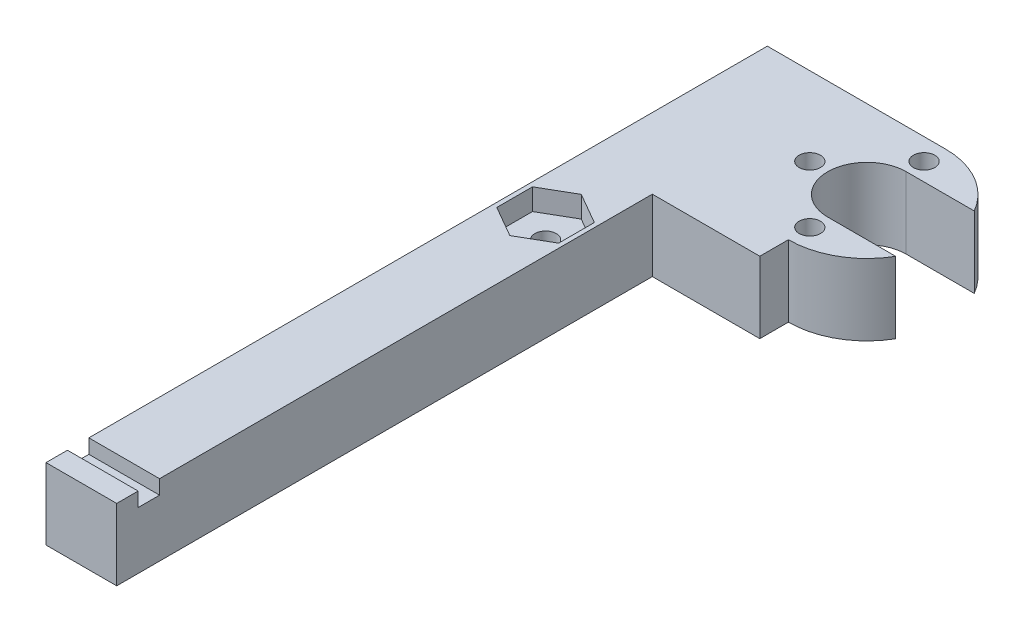
SolidWorks part; units mm, degrees
ref_plane "Front Plane" through (0, 0, 0) normal (0, 0, 1) x (1, 0, 0)
ref_plane "Top Plane" through (0, 0, 0) normal (0, 1, 0) x (1, 0, 0)
ref_plane "Right Plane" through (0, 0, 0) normal (1, 0, 0) x (0, 0, -1)
sketch "Sketch1" plane through (0, 0, 0) normal (0, 1, 0) x (1, 0, 0)
  line L0 (0, 0) -> (0, -75)
  line L1 (0, -75) -> (9.9, -75)
  line L2 (9.9, -75) -> (9.9, 0)
  line L3 (9.9, 0) -> (24.95, 0)
  line L4 (24.95, 0) -> (24.95, 4)
  line L5 (0, 0) -> (0, 26)
  line L6 (0, 26) -> (24.95, 26)
  circle A0 centre (24.95, 15) radius 5.5
  arc A1 (24.95, 4) -> (24.95, 26) centre (24.95, 15) ccw
  circle A2 centre (24.95, 23) radius 1.5
  circle A3 centre (24.95, 7) radius 1.5
  circle A4 centre (16.95, 15) radius 1.5
  point P7 (4.95, -75)
  dimension "D5" = 11
  dimension "D6" = 11
  dimension "D7" = 3
  dimension "D9" = 3
  dimension "D11" = 3
  dimension "D1" = 75
  dimension "D2" = 9.9
  dimension "D3" = 20
  dimension "D4" = 15
  dimension "D8" = 8
  dimension "D10" = 8
  dimension "D12" = 8
extrude "Boss-Extrude1" add sketch "Sketch1" along normal blind 10
sketch "Sketch2" plane through (0, 10, 0) normal (0, 1, 0) x (1, 0, 0)
  line L0 (0, 26) -> (0, -75) construction
  line L1 (0, -69) -> (9.9, -69)
  line L2 (0, -69) -> (0, -72)
  line L3 (0, -72) -> (9.9, -72)
  line L4 (9.9, -69) -> (9.9, -72)
  line L5 (9.9, -75) -> (9.9, 0) construction
  dimension "D1" = 3
  dimension "D2" = 3
extrude "Cut-Extrude1" cut sketch "Sketch2" against normal blind 2
sketch "Sketch3" plane through (0, 10, 0) normal (0, 1, 0) x (1, 0, 0)
  line L1 (24.95, 20.5) -> (45.0563, 20.5)
  line L2 (24.95, 20.5) -> (24.95, 9.5)
  line L3 (24.95, 9.5) -> (45.0563, 9.5)
  line L4 (45.0563, 20.5) -> (45.0563, 9.5)
  circle A0 centre (24.95, 15) radius 5.5 construction
extrude "Cut-Extrude2" cut sketch "Sketch3" against normal blind 10
sketch "Sketch4" plane through (0, 10, 0) normal (0, 1, 0) x (1, 0, 0)
  circle A0 centre (4.95, -10) radius 1.5
  dimension "D2" = 3
  dimension "D1" = 10
extrude "Cut-Extrude3" cut sketch "Sketch4" against normal blind 10
sketch "Sketch5" plane through (0, 10, 0) normal (0, 1, 0) x (1, 0, 0)
  line L1 (4.95, -5) -> (0.6199, -7.5)
  line L2 (0.6199, -7.5) -> (0.6199, -12.5)
  line L3 (0.6199, -12.5) -> (4.95, -15)
  line L4 (4.95, -15) -> (9.2801, -12.5)
  line L5 (9.2801, -12.5) -> (9.2801, -7.5)
  line L6 (9.2801, -7.5) -> (4.95, -5)
  circle A0 centre (4.95, -10) radius 4.3301 construction
  dimension "D1" = 5
extrude "Cut-Extrude4" cut sketch "Sketch5" against normal blind 3
